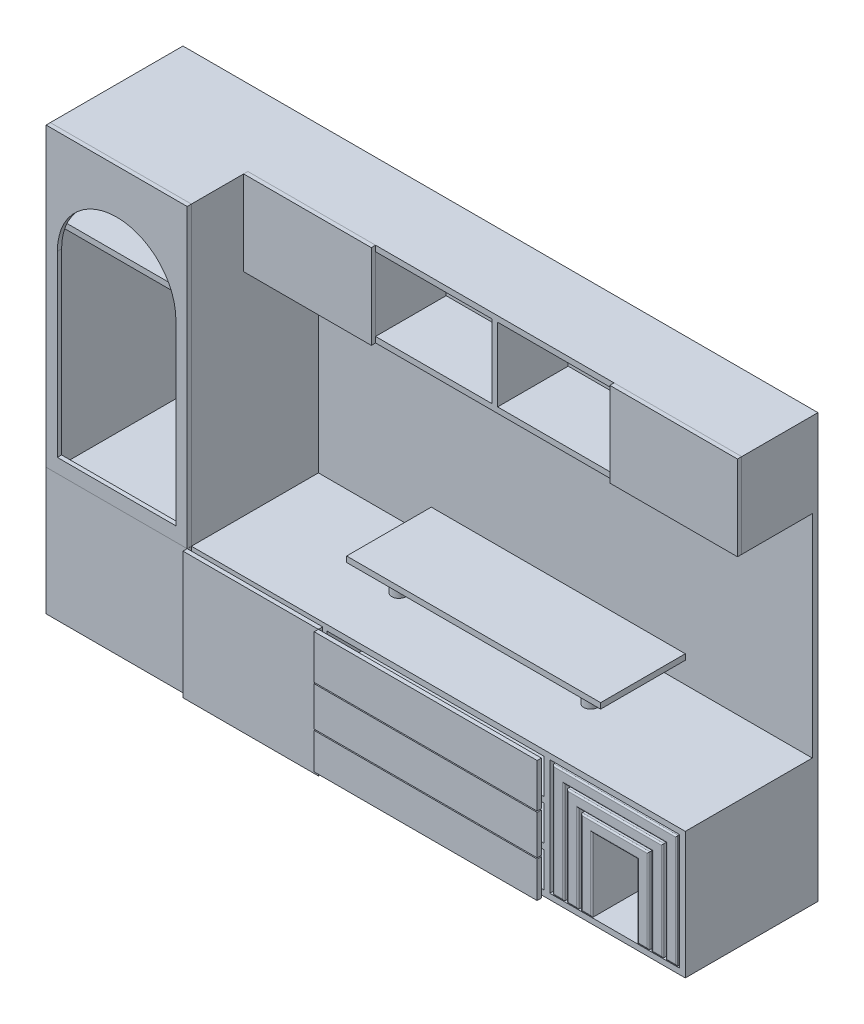
SolidWorks part; units mm, degrees
material "Oak"
ref_plane "Front Plane" through (0, 0, 0) normal (0, 0, 1) x (1, 0, 0)
ref_plane "Top Plane" through (0, 0, 0) normal (0, 1, 0) x (1, 0, 0)
ref_plane "Right Plane" through (0, 0, 0) normal (1, 0, 0) x (0, 0, -1)
sketch "Sketch1" plane through (0, 0, 0) normal (0, 0, 1) x (1, 0, 0)
  line L1 (1125, -750) -> (-1125, -750)
  line L2 (1125, -750) -> (1125, 750)
  line L3 (1125, 750) -> (-1125, 750)
  line L4 (-1125, -750) -> (-1125, 750)
  line L5 (1125, -750) -> (-1125, 750) construction
  line L6 (1125, 750) -> (-1125, -750) construction
  point P0 (0, 0)
  dimension "D1" = 1500
  dimension "D2" = 2250
extrude "Boss-Extrude1" add sketch "Sketch1" along normal blind 20
sketch "Sketch2" plane through (0, 0, 20) normal (0, 0, 1) x (1, 0, 0)
  line L0 (-625, 750) -> (-625, -300)
  line L3 (1125, 750) -> (-1125, 750) construction
  line L4 (-1125, -750) -> (1125, -750) construction
  line L5 (-625, -300) -> (1125, -300)
  line L6 (1125, -750) -> (1125, 750) construction
  line L7 (-1125, 750) -> (-1125, -750) construction
  line L8 (1125, -750) -> (1125, -300)
  line L9 (-1125, -750) -> (1125, -750)
  line L10 (-1125, 750) -> (-1125, -750)
  line L11 (-625, 750) -> (-1125, 750)
  dimension "D1" = 500
  dimension "D2" = 450
extrude "Boss-Extrude2" add sketch "Sketch2" along normal blind 450
sketch "Sketch4" plane through (0, 0, 20) normal (0, 0, 1) x (1, 0, 0)
  line L0 (1125, -300) -> (1125, 750) construction
  line L1 (-625, 750) -> (1125, 750)
  line L2 (-625, 750) -> (-625, 450)
  line L3 (-625, 450) -> (1125, 450)
  line L4 (1125, 750) -> (1125, 450)
  dimension "D1" = 300
extrude "Boss-Extrude3" add sketch "Sketch4" along normal blind 250
sketch "Sketch5" plane through (0, 0, 270) normal (0, 0, 1) x (1, 0, 0)
  line L0 (-625, -300) -> (-625, 750) construction
  line L1 (-605, 730) -> (-192.5, 730)
  line L2 (-605, 730) -> (-605, 470)
  line L3 (-605, 470) -> (-192.5, 470)
  line L4 (-192.5, 730) -> (-192.5, 470)
  line L5 (1125, 750) -> (-625, 750) construction
  line L6 (-625, 450) -> (1125, 450) construction
  line L7 (1125, 450) -> (1125, 750) construction
  line L8 (-172.5, 730) -> (240, 730)
  line L9 (-172.5, 730) -> (-172.5, 470)
  line L10 (-172.5, 470) -> (240, 470)
  line L11 (240, 730) -> (240, 470)
  line L12 (260, 730) -> (672.5, 730)
  line L13 (260, 730) -> (260, 470)
  line L14 (260, 470) -> (672.5, 470)
  line L15 (672.5, 730) -> (672.5, 470)
  line L16 (692.5, 730) -> (1105, 730)
  line L17 (692.5, 730) -> (692.5, 470)
  line L18 (692.5, 470) -> (1105, 470)
  line L19 (1105, 730) -> (1105, 470)
  dimension "D1" = 20
  dimension "D2" = 20
  dimension "D3" = 20
  dimension "D4" = 20
  dimension "D5" = 20
  dimension "D6" = 20
  dimension "D7" = 20
extrude "Cut-Extrude1" cut sketch "Sketch5" against normal up to surface (250 mm away) up to face at (250, 75, 20)
sketch "Sketch6" plane through (0, 0, 470) normal (0, 0, 1) x (1, 0, 0)
  line L0 (-625, 750) -> (-1125, 750) construction
  line L1 (-645, 730) -> (-1105, 730)
  line L2 (-645, 730) -> (-645, 470)
  line L3 (-645, 470) -> (-1105, 470)
  line L4 (-1105, 730) -> (-1105, 470)
  line L5 (-625, -300) -> (-625, 750) construction
  line L6 (-1125, 750) -> (-1125, -750) construction
  line L7 (-605, 470) -> (-192.5, 470) construction
  line L8 (1125, -300) -> (-625, -300) construction
  line L9 (-645, 450) -> (-1105, 450)
  line L10 (-645, 450) -> (-645, -300)
  line L11 (-645, -300) -> (-1105, -300)
  line L12 (-1105, 450) -> (-1105, -300)
  line L13 (-645, -320) -> (-1105, -320)
  line L14 (-645, -320) -> (-645, -730)
  line L15 (-645, -730) -> (-1105, -730)
  line L16 (-1105, -320) -> (-1105, -730)
  line L17 (-1125, -750) -> (1125, -750) construction
  line L18 (-625, -300) -> (-625, 450) construction
  line L19 (1125, -300) -> (-625, -300) construction
  line L20 (-625, -320) -> (-165, -320)
  line L21 (-625, -320) -> (-625, -730)
  line L22 (-625, -730) -> (-165, -730)
  line L23 (-165, -320) -> (-165, -730)
  line L24 (1125, -750) -> (1125, -300) construction
  line L25 (1105, -320) -> (645, -320)
  line L26 (1105, -320) -> (1105, -730)
  line L27 (1105, -730) -> (645, -730)
  line L28 (645, -320) -> (645, -730)
  line L30 (-145, -320) -> (625, -320)
  line L31 (-145, -320) -> (-145, -443.3333)
  line L32 (-145, -443.3333) -> (625, -443.3333)
  line L33 (625, -320) -> (625, -443.3333)
  line L34 (-145, -463.3333) -> (625, -463.3333)
  line L35 (-145, -463.3333) -> (-145, -586.6667)
  line L36 (-145, -586.6667) -> (625, -586.6667)
  line L37 (625, -463.3333) -> (625, -586.6667)
  line L38 (-145, -606.6667) -> (625, -606.6667)
  line L39 (-145, -606.6667) -> (-145, -730)
  line L40 (-145, -730) -> (625, -730)
  line L41 (625, -606.6667) -> (625, -730)
  point P50 (-165, -525)
  dimension "D1" = 20
  dimension "D2" = 20
  dimension "D3" = 20
  dimension "D4" = 0
  dimension "D5" = 0
  dimension "D6" = 20
  dimension "D7" = 20
  dimension "D8" = 20
  dimension "D9" = 20
  dimension "D10" = 20
  dimension "D11" = 20
  dimension "D12" = 20
  dimension "D13" = 20
  dimension "D14" = 20
  dimension "D15" = 20
  dimension "D16" = 20
  dimension "D17" = 20
  dimension "D18" = 20
  dimension "D19" = 20
  dimension "D20" = 20
  dimension "D21" = 20
  dimension "D22" = 20
  dimension "D23" = 20
  dimension "D24" = 20
  dimension "D25" = 20
  dimension "D26" = 20
  dimension "D27" = 20
  dimension "D28" = 20
extrude "Cut-Extrude2" cut sketch "Sketch6" against normal up to surface (450 mm away) up to face at (250, 75, 20)
sketch "Sketch7" plane through (0, 0, 20) normal (0, 0, 1) x (1, 0, 0)
  line L0 (1125, -300) -> (-625, -300) construction
  line L1 (-225, -205) -> (675, -205)
  line L2 (-225, -205) -> (-225, -225)
  line L3 (-225, -225) -> (675, -225)
  line L4 (675, -205) -> (675, -225)
  line L6 (1125, -300) -> (1125, 450) construction
  dimension "D1" = 900
  dimension "D2" = 20
  dimension "D3" = 75
  dimension "D4" = 450
extrude "Boss-Extrude6" add sketch "Sketch7" along normal blind 300 separate body
sketch "Sketch10" plane through (0, -225, 0) normal (0, -1, 0) x (1, 0, 0)
  line L0 (625, 20) -> (-145, 20) construction
  line L1 (-225, 320) -> (675, 320) construction
  line L2 (-225, 320) -> (-225, 20) construction
  line L3 (675, 320) -> (675, 20) construction
  circle A0 centre (-115, 245) radius 25
  circle A1 centre (-115, 95) radius 25
  circle A2 centre (565, 245) radius 25
  circle A3 centre (565, 95) radius 25
  dimension "D1" = 50
  dimension "D2" = 75
  dimension "D3" = 75
  dimension "D4" = 75
  dimension "D5" = 75
  dimension "D6" = 110
  dimension "D7" = 110
  dimension "D8" = 110
  dimension "D9" = 110
extrude "Boss-Extrude7" add sketch "Sketch10" along normal blind 100
sketch "Sketch11" plane through (0, 0, 20) normal (0, 0, 1) x (1, 0, 0)
  line L0 (645, -730) -> (1105, -730) construction
  line L1 (655, -330) -> (1095, -330)
  line L2 (655, -330) -> (655, -730)
  line L4 (1095, -330) -> (1095, -730)
  line L5 (1105, -320) -> (645, -320) construction
  line L6 (1105, -320) -> (1105, -730) construction
  line L7 (645, -320) -> (645, -730) construction
  line L8 (695, -370) -> (695, -730)
  line L9 (695, -370) -> (1055, -370)
  line L10 (1055, -370) -> (1055, -730)
  line L11 (705, -380) -> (705, -730)
  line L12 (705, -380) -> (1045, -380)
  line L13 (1045, -380) -> (1045, -730)
  line L14 (745, -420) -> (745, -730)
  line L15 (745, -420) -> (1005, -420)
  line L16 (1005, -420) -> (1005, -730)
  line L17 (755, -430) -> (755, -730)
  line L18 (755, -430) -> (995, -430)
  line L19 (995, -430) -> (995, -730)
  line L20 (795, -470) -> (795, -730)
  line L21 (795, -470) -> (955, -470)
  line L22 (955, -470) -> (955, -730)
  line L23 (655, -730) -> (695, -730)
  line L24 (695, -730) -> (705, -730)
  line L25 (705, -730) -> (745, -730)
  line L26 (745, -730) -> (755, -730)
  line L27 (755, -730) -> (795, -730)
  line L28 (795, -730) -> (955, -730)
  line L29 (955, -730) -> (995, -730)
  line L30 (995, -730) -> (1005, -730)
  line L31 (1005, -730) -> (1045, -730)
  line L32 (1045, -730) -> (1055, -730)
  line L33 (1055, -730) -> (1095, -730)
  line M16 (645, -730) -> (1105, -730)
  dimension "D1" = 10
  dimension "D2" = 10
  dimension "D3" = 10
  dimension "D4" = 40
  dimension "D5" = 10
  dimension "D6" = 40
  dimension "D7" = 10
  dimension "D8" = 40
extrude "Boss-Extrude8" add sketch "Sketch11" along normal up to surface (450 mm away) separate body contours L9 L10 L4 L1 L2 L8 M16 | L15 L16 L13 L12 L11 L14 M16 | L21 L22 L19 L18 L17 L20 M16 up to face at (-875, 600, 470)
fillet "Fillet1" radius 5 8 edges at (675, -730, 470) (655, -530, 470) (875, -330, 470) (1095, -530, 470) (1075, -730, 470) (1055, -550, 470) (875, -370, 470) (695, -550, 470)
fillet "Fillet2" radius 5 8 edges at (725, -730, 470) (705, -555, 470) (875, -380, 470) (1045, -555, 470) (1025, -730, 470) (1005, -575, 470) (875, -420, 470) (745, -575, 470)
fillet "Fillet3" radius 5 8 edges at (775, -730, 470) (755, -580, 470) (875, -430, 470) (995, -580, 470) (975, -730, 470) (955, -600, 470) (875, -470, 470) (795, -600, 470)
sketch "Sketch13" plane through (0, 0, 270) normal (0, 0, 1) x (1, 0, 0)
  line L0 (-625, 450) -> (1125, 450) construction
  line L1 (-625, 750) -> (-172.5, 750)
  line L2 (-625, 750) -> (-625, 450)
  line L3 (-625, 450) -> (-172.5, 450)
  line L4 (-172.5, 750) -> (-172.5, 450)
  line L5 (1125, 750) -> (672.5, 750)
  line L6 (1125, 750) -> (1125, 450)
  line L7 (1125, 450) -> (672.5, 450)
  line L8 (672.5, 750) -> (672.5, 450)
  line L9 (-625, 450) -> (1125, 450) construction
  line L10 (-172.5, 470) -> (-172.5, 730) construction
  line L11 (672.5, 470) -> (672.5, 730) construction
  point P12 (-177.7189, 450)
  dimension "D1" = 0
  dimension "D2" = 0
extrude "Boss-Extrude9" add sketch "Sketch13" along normal blind 15 separate body
sketch "Sketch14" plane through (0, 0, 470) normal (0, 0, 1) x (1, 0, 0)
  line L0 (-625, -300) -> (-625, 450) construction
  line L1 (-1125, 750) -> (-625, 750)
  line L2 (-1125, 750) -> (-1125, -300)
  line L3 (-1125, -300) -> (-625, -300)
  line L4 (-625, 750) -> (-625, -300)
  line L5 (1125, -300) -> (-625, -300) construction
  dimension "D1" = 0
extrude "Boss-Extrude10" add sketch "Sketch14" along normal blind 15 separate body
sketch "Sketch15" plane through (0, 0, 470) normal (0, 0, 1) x (1, 0, 0)
  line L0 (-1125, -750) -> (1125, -750) construction
  line L1 (-1125, -300) -> (-624.7646, -300)
  line L2 (-1125, -300) -> (-1125, -750)
  line L3 (-1125, -750) -> (-624.7646, -750)
  line L4 (-624.7646, -300) -> (-624.7646, -750)
extrude "Boss-Extrude11" add sketch "Sketch15" along normal blind 15 separate body
sketch "Sketch16" plane through (0, 0, 485) normal (0, 0, 1) x (1, 0, 0)
  line L0 (-1125, -750) -> (1125, -750) construction
  line L1 (-625, -300) -> (-145, -300)
  line L2 (-625, -300) -> (-625, -750)
  line L3 (-625, -750) -> (-145, -750)
  line L4 (-145, -300) -> (-145, -750)
  line L5 (-145, -606.6667) -> (-145, -730) construction
  dimension "D1" = 0
extrude "Boss-Extrude12" add sketch "Sketch16" along normal blind 15 separate body
sketch "Sketch17" plane through (0, 0, 500) normal (0, 0, 1) x (1, 0, 0)
  line L0 (-145, -750) -> (-145, -300) construction
  line L1 (-145, -300) -> (645, -300)
  line L2 (-145, -300) -> (-145, -455.3333)
  line L3 (-145, -455.3333) -> (645, -455.3333)
  line L4 (645, -300) -> (645, -455.3333)
  line L5 (-145, -459.3333) -> (645, -459.3333)
  line L6 (-145, -459.3333) -> (-145, -598.6667)
  line L7 (-145, -598.6667) -> (645, -598.6667)
  line L8 (645, -459.3333) -> (645, -598.6667)
  line L9 (625, -606.6667) -> (-145, -606.6667) construction
  line L10 (-145, -602.6667) -> (645, -602.6667)
  line L11 (-145, -602.6667) -> (-145, -730)
  line L12 (-145, -730) -> (645, -730)
  line L13 (645, -602.6667) -> (645, -730)
  line L14 (625, -463.3333) -> (-145, -463.3333) construction
  line L15 (645, -320) -> (645, -730) construction
  dimension "D1" = 4
  dimension "D2" = 4
  dimension "D3" = 8
  dimension "D4" = 8
  dimension "D5" = 0
extrude "Boss-Extrude13" add sketch "Sketch17" along normal blind 15 separate body
sketch "Sketch18" plane through (0, 0, 485) normal (0, 0, 1) x (1, 0, 0)
  line L0 (-1125, -300) -> (-625, -300) construction
  line L2 (-1085, 382.6063) -> (-1085, -250)
  line L3 (-1085, -250) -> (-665, -250)
  line L4 (-665, 382.6063) -> (-665, -250)
  line L5 (-1125, 750) -> (-1125, -300) construction
  line L6 (-625, -300) -> (-625, 750) construction
  arc A0 (-665, 382.6063) -> (-1085, 382.6063) centre (-875, 382.6063) ccw
  point P11 (-1085, 457.7851)
  point P12 (-665, 457.7851)
  point P13 (-1085, 382.6063)
  point P14 (-665, 382.6063)
  point P15 (0, 0)
  dimension "D1" = 50
  dimension "D2" = 40
  dimension "D3" = 40
extrude "Cut-Extrude3" cut sketch "Sketch18" against normal blind 15
